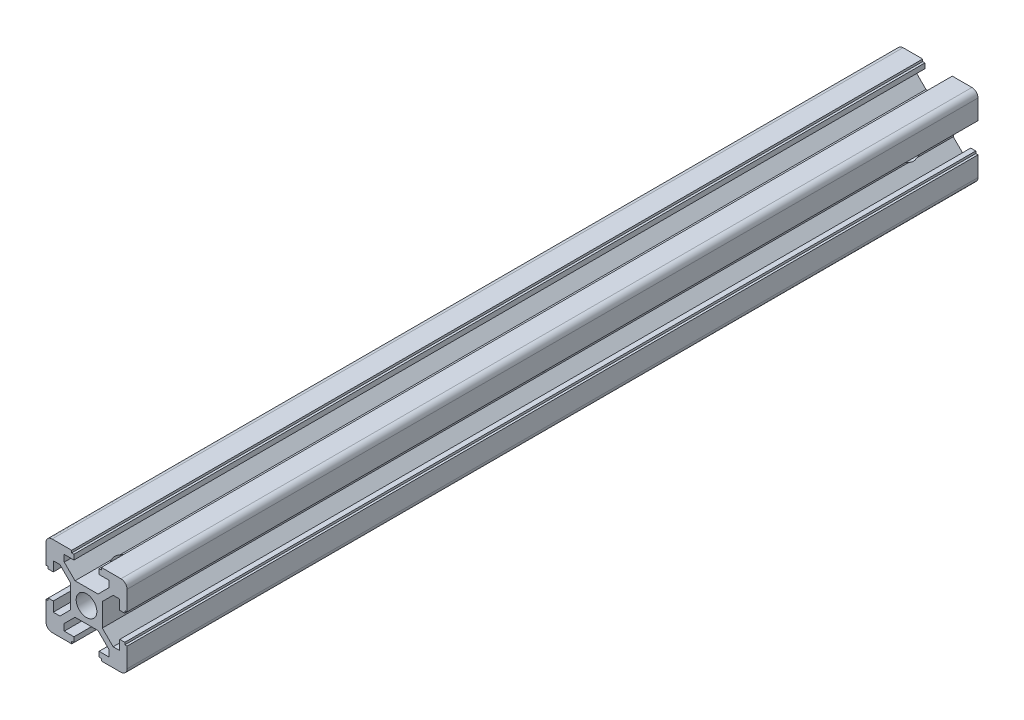
SolidWorks part; units mm, degrees
material "6063-T5"
ref_plane "前视基准面" through (0, 0, 0) normal (0, 0, 1) x (1, 0, 0)
ref_plane "上视基准面" through (0, 0, 0) normal (0, 1, 0) x (1, 0, 0)
ref_plane "右视基准面" through (0, 0, 0) normal (1, 0, 0) x (0, 0, -1)
sketch "草图2" plane through (0, 0, 0) normal (0, 0, 1) x (1, 0, 0)
  line L0 (-3.9, 2.8393) -> (-6.5607, 5.5)
  line L1 (-2.8393, 3.9) -> (2.8393, 3.9)
  line L2 (-3.9, 2.8393) -> (-3.9, -2.8393)
  line L3 (-2.8393, -3.9) -> (2.8393, -3.9)
  line L4 (3.9, 2.8393) -> (3.9, -2.8393)
  line L5 (-3.9, 3.9) -> (3.9, -3.9) construction
  line L6 (-3.9, -3.9) -> (3.9, 3.9) construction
  line L7 (-2.8393, 3.9) -> (-5.5, 6.5607)
  line L8 (-5.5, 6.5607) -> (-5.5, 8.2)
  line L9 (-5.5, 8.2) -> (-3.1, 8.2)
  line L10 (-3.1, 8.2) -> (-3.1, 9.45)
  line L11 (-3.1, 9.45) -> (-3.65, 9.45)
  line L12 (-3.65, 9.45) -> (-3.65, 10)
  line L13 (-3.65, 10) -> (-8.5, 10)
  line L14 (-6.5607, 5.5) -> (-8.2, 5.5)
  line L15 (-10, 3.65) -> (-10, 8.5)
  line L16 (-9.45, 3.65) -> (-10, 3.65)
  line L17 (-9.45, 3.1) -> (-9.45, 3.65)
  line L18 (-8.2, 3.1) -> (-9.45, 3.1)
  line L19 (-8.2, 5.5) -> (-8.2, 3.1)
  line L20 (2.8393, 3.9) -> (5.5, 6.5607)
  line L21 (3.9, 2.8393) -> (6.5607, 5.5)
  line L22 (6.5607, 5.5) -> (8.2, 5.5)
  line L23 (8.2, 5.5) -> (8.2, 3.1)
  line L24 (8.2, 3.1) -> (9.45, 3.1)
  line L25 (9.45, 3.1) -> (9.45, 3.65)
  line L26 (9.45, 3.65) -> (10, 3.65)
  line L27 (10, 3.65) -> (10, 8.5)
  line L28 (5.5, 6.5607) -> (5.5, 8.2)
  line L29 (3.65, 10) -> (8.5, 10)
  line L30 (3.65, 9.45) -> (3.65, 10)
  line L31 (3.1, 9.45) -> (3.65, 9.45)
  line L32 (3.1, 8.2) -> (3.1, 9.45)
  line L33 (5.5, 8.2) -> (3.1, 8.2)
  line L34 (3.9, -2.8393) -> (6.5607, -5.5)
  line L35 (2.8393, -3.9) -> (5.5, -6.5607)
  line L36 (5.5, -6.5607) -> (5.5, -8.2)
  line L37 (5.5, -8.2) -> (3.1, -8.2)
  line L38 (3.1, -8.2) -> (3.1, -9.45)
  line L39 (3.1, -9.45) -> (3.65, -9.45)
  line L40 (3.65, -9.45) -> (3.65, -10)
  line L41 (3.65, -10) -> (8.5, -10)
  line L42 (6.5607, -5.5) -> (8.2, -5.5)
  line L43 (10, -3.65) -> (10, -8.5)
  line L44 (9.45, -3.65) -> (10, -3.65)
  line L45 (9.45, -3.1) -> (9.45, -3.65)
  line L46 (8.2, -3.1) -> (9.45, -3.1)
  line L47 (8.2, -5.5) -> (8.2, -3.1)
  line L48 (-2.8393, -3.9) -> (-5.5, -6.5607)
  line L49 (-3.9, -2.8393) -> (-6.5607, -5.5)
  line L50 (-6.5607, -5.5) -> (-8.2, -5.5)
  line L51 (-8.2, -5.5) -> (-8.2, -3.1)
  line L52 (-8.2, -3.1) -> (-9.45, -3.1)
  line L53 (-9.45, -3.1) -> (-9.45, -3.65)
  line L54 (-9.45, -3.65) -> (-10, -3.65)
  line L55 (-10, -3.65) -> (-10, -8.5)
  line L56 (-5.5, -6.5607) -> (-5.5, -8.2)
  line L57 (-3.65, -10) -> (-8.5, -10)
  line L58 (-3.65, -9.45) -> (-3.65, -10)
  line L59 (-3.1, -9.45) -> (-3.65, -9.45)
  line L60 (-3.1, -8.2) -> (-3.1, -9.45)
  line L61 (-5.5, -8.2) -> (-3.1, -8.2)
  circle A0 centre (0, 0) radius 2.55
  arc A1 (-8.5, 10) -> (-10, 8.5) centre (-8.5, 8.5) ccw
  arc A2 (10, 8.5) -> (8.5, 10) centre (8.5, 8.5) ccw
  arc A3 (8.5, -10) -> (10, -8.5) centre (8.5, -8.5) ccw
  arc A4 (-10, -8.5) -> (-8.5, -10) centre (-8.5, -8.5) ccw
  point P25 (-10, 10)
  point P79 (0, 0)
  dimension "D1" = 5.1
  dimension "D9" = 1.5
  dimension "D2" = 7.8
  dimension "D3" = 1.5
  dimension "D4" = 10
  dimension "D5" = 3.1
  dimension "D6" = 0.55
  dimension "D7" = 1.8
  dimension "D8" = 5.5
  dimension "D11" = 3.9
  dimension "D10" = 4
extrude "凸台-拉伸1" add sketch "草图2" along normal blind 210
sketch "草图3" plane through (-10, 0, 0) normal (1, 0, 0) x (0, 1, 0)
  line L0 (-3.65, 0) -> (-8.5, 0) construction
  line L2 (0, 0) -> (0, 10) construction
  circle A0 centre (0, 10) radius 3
  dimension "D1" = 6
  dimension "D2" = 10
extrude "切除-拉伸1" cut sketch "草图3" along normal through all
sketch "草图4" plane through (0, -10, 0) normal (0, -1, 0) x (1, 0, 0)
  line L0 (-8.5, 210) -> (-3.65, 210) construction
  line L1 (0, 200) -> (0, 210) construction
  line L2 (-2.8393, 210) -> (2.8393, 210) construction
  circle A0 centre (0, 200) radius 3
  dimension "D1" = 6
  dimension "D2" = 10
extrude "切除-拉伸2" cut sketch "草图4" against normal through all
sketch "草图5" plane through (-10, 0, 0) normal (-1, 0, 0) x (0, 0, 1)
  circle A0 centre (101, 0) radius 2.5
  circle A1 centre (142, 0) radius 2.5
  dimension "D1" = 5
  dimension "D2" = 5
extrude "切除-拉伸3" cut sketch "草图5" against normal through all
